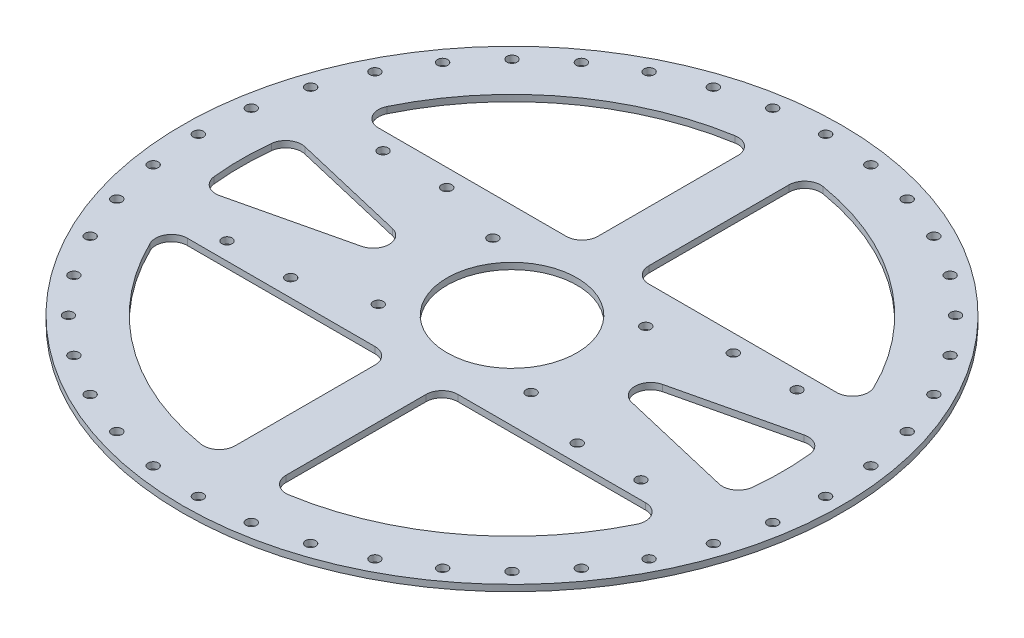
SolidWorks part; units mm, degrees
material "Thornel Mat VMA"
ref_plane "前视基准面" through (0, 0, 0) normal (0, 0, 1) x (1, 0, 0)
ref_plane "上视基准面" through (0, 0, 0) normal (0, 1, 0) x (1, 0, 0)
ref_plane "右视基准面" through (0, 0, 0) normal (1, 0, 0) x (0, 0, -1)
sketch "草图1" plane through (0, 0, 0) normal (0, 1, 0) x (1, 0, 0)
  line L1 (-24, 18) -> (24, 18) construction
  line L2 (-24, 18) -> (-24, -18) construction
  line L3 (-24, -18) -> (24, -18) construction
  line L4 (24, 18) -> (24, -18) construction
  line L5 (-24, 18) -> (24, -18) construction
  line L6 (-24, -18) -> (24, 18) construction
  circle A0 centre (-24, -18) radius 1.6
  circle A1 centre (24, -18) radius 1.6
  circle A2 centre (24, 18) radius 1.6
  circle A3 centre (-24, 18) radius 1.6
  circle A4 centre (0, 0) radius 103.5
  point P0 (0, 0)
  dimension "D3" = 3.2
  dimension "D4" = 207
  dimension "D1" = 48
  dimension "D2" = 36
extrude "凸台-拉伸1" add sketch "草图1" along normal blind 2
sketch "草图2" plane through (0, 2, 0) normal (0, 1, 0) x (1, 0, 0)
  line L0 (-55, 0) -> (55, 0) construction
  line L1 (-55, -24.5) -> (55, -24.5) construction
  line L2 (-55, 24.5) -> (55, 24.5) construction
  line L3 (-100, 0) -> (55, 0) construction
  line L4 (-100, -24.5) -> (55, -24.5) construction
  line L5 (-100, 24.5) -> (55, 24.5) construction
  line L6 (-65, 24.5) -> (-45, 24.5) construction
  line L7 (45, 24.5) -> (65, 24.5) construction
  line L8 (65, -24.5) -> (45, -24.5) construction
  line L9 (-65, -24.5) -> (-45, -24.5) construction
  circle A0 centre (0, 0) radius 98.5 construction
  circle A1 centre (-45, 24.5) radius 1.6
  circle A2 centre (-65, 24.5) radius 1.6
  circle A3 centre (-65, -24.5) radius 1.6
  circle A4 centre (-45, -24.5) radius 1.6
  circle A5 centre (45, -24.5) radius 1.6
  circle A6 centre (65, -24.5) radius 1.6
  circle A7 centre (45, 24.5) radius 1.6
  circle A8 centre (65, 24.5) radius 1.6
  circle A9 centre (0, 98.5) radius 1.6
  circle A10 centre (15.4088, 97.2873) radius 1.6
  circle A11 centre (30.4382, 93.6791) radius 1.6
  circle A12 centre (44.7181, 87.7641) radius 1.6
  circle A13 centre (57.8968, 79.6882) radius 1.6
  circle A14 centre (69.65, 69.65) radius 1.6
  circle A15 centre (79.6882, 57.8968) radius 1.6
  circle A16 centre (87.7641, 44.7181) radius 1.6
  circle A17 centre (93.6791, 30.4382) radius 1.6
  circle A18 centre (97.2873, 15.4088) radius 1.6
  circle A19 centre (98.5, 0) radius 1.6
  circle A20 centre (97.2873, -15.4088) radius 1.6
  circle A21 centre (93.6791, -30.4382) radius 1.6
  circle A22 centre (87.7641, -44.7181) radius 1.6
  circle A23 centre (79.6882, -57.8968) radius 1.6
  circle A24 centre (69.65, -69.65) radius 1.6
  circle A25 centre (57.8968, -79.6882) radius 1.6
  circle A26 centre (44.7181, -87.7641) radius 1.6
  circle A27 centre (30.4382, -93.6791) radius 1.6
  circle A28 centre (15.4088, -97.2873) radius 1.6
  circle A29 centre (0, -98.5) radius 1.6
  circle A30 centre (-15.4088, -97.2873) radius 1.6
  circle A31 centre (-30.4382, -93.6791) radius 1.6
  circle A32 centre (-44.7181, -87.7641) radius 1.6
  circle A33 centre (-57.8968, -79.6882) radius 1.6
  circle A34 centre (-69.65, -69.65) radius 1.6
  circle A35 centre (-79.6882, -57.8968) radius 1.6
  circle A36 centre (-87.7641, -44.7181) radius 1.6
  circle A37 centre (-93.6791, -30.4382) radius 1.6
  circle A38 centre (-97.2873, -15.4088) radius 1.6
  circle A39 centre (-98.5, 0) radius 1.6
  circle A40 centre (-97.2873, 15.4088) radius 1.6
  circle A41 centre (-93.6791, 30.4382) radius 1.6
  circle A42 centre (-87.7641, 44.7181) radius 1.6
  circle A43 centre (-79.6882, 57.8968) radius 1.6
  circle A44 centre (-69.65, 69.65) radius 1.6
  circle A45 centre (-57.8968, 79.6882) radius 1.6
  circle A46 centre (-44.7181, 87.7641) radius 1.6
  circle A47 centre (-30.4382, 93.6791) radius 1.6
  circle A48 centre (-15.4088, 97.2873) radius 1.6
  point P32 (116.4998, -20.0917)
  point P33 (0, 0)
  point P111 (0, 0)
  dimension "D5" = 3.2
  dimension "D6" = 197
  dimension "D7" = 3.2
  dimension "D3" = 110
  dimension "D4" = 20
  dimension "D1" = 24.5
  dimension "D2" = 24.5
  dimension "D8" = 40
extrude "切除-拉伸1" cut sketch "草图2" against normal through all
sketch "草图3" plane through (0, 2, 0) normal (0, 1, 0) x (1, 0, 0)
  line L0 (0, -85) -> (0, 85)
  line L1 (-85, 0) -> (85, 0)
  line L2 (8, -85) -> (8, 85)
  line L3 (-85, -8) -> (85, -8)
  line L4 (-8, -85) -> (-8, 85)
  line L5 (-85, 8) -> (85, 8)
  line L6 (-85, -30) -> (85, -30)
  line L7 (-85, 30) -> (85, 30)
  circle A0 centre (-24, 18) radius 1.6 construction
  circle A1 centre (24, 18) radius 1.6 construction
  circle A2 centre (24, -18) radius 1.6 construction
  circle A3 centre (-24, -18) radius 1.6 construction
  circle A4 centre (-24, 18) radius 1.6 construction
  circle A5 centre (24, 18) radius 1.6 construction
  circle A6 centre (24, -18) radius 1.6 construction
  circle A7 centre (-24, -18) radius 1.6 construction
  circle A8 centre (-24, 18) radius 9.6
  circle A9 centre (24, 18) radius 9.6
  circle A10 centre (24, -18) radius 9.6
  circle A11 centre (-24, -18) radius 9.6
  circle A12 centre (0, 0) radius 20.4
  circle A13 centre (0, 0) radius 85
  dimension "D2" = 170
  dimension "D1" = 8
  dimension "D3" = 8
  dimension "D4" = 8
  dimension "D5" = 30
  dimension "D6" = 30
extrude "切除-拉伸2" cut sketch "草图3" against normal blind 10 contours L6 A13 L4 | L2 A13 L6 | L7 A13 L2 | L4 A13 L7 | L4 A12 L5 | L5 A12 L1 L4 | L1 A12 L3 L4 | L3 A12 L4 | L4 A12 L0 L3 | L0 A12 L2 L3 | L0 L3 L2 L1 | L4 L3 L0 L1 | L5 L4 L1 L0 | L5 L0 L1 L2 | L2 A12 L0 L5 | L0 A12 L4 L5 | L5 A12 L2 | L1 A12 L5 L2 | L3 A12 L1 L2 | L2 A12 L3
sketch "草图4" plane through (0, 0, 0) normal (0, -1, 0) x (1, 0, 0)
  line L0 (-83.8801, -14.6334) -> (81.5859, 24.3666)
  line L1 (-82.733, 19.5) -> (82.733, 19.5)
  line L3 (-82.733, -19.5) -> (82.733, -19.5)
  line L5 (-82.733, 19.5) -> (82.733, -19.5) construction
  line L6 (-82.733, -19.5) -> (82.733, 19.5) construction
  line L7 (-81.5859, 24.3666) -> (83.8801, -14.6334)
  line L8 (-81.5859, -24.3666) -> (83.8801, 14.6334)
  line L9 (-83.8801, 14.6334) -> (81.5859, -24.3666)
  circle A0 centre (65, 24.5) radius 1.6 construction
  circle A1 centre (0, 0) radius 85
  point P0 (0, 0)
  point P10 (0, 0)
  point P12 (82.733, -19.5)
  dimension "D2" = 170
  dimension "D1" = 5
  dimension "D3" = 5
  dimension "D4" = 5
extrude "切除-拉伸3" cut sketch "草图4" against normal blind 10 contours L9 A1 L0 | L7 A1 L8
fillet "圆角1" radius 5 18 edges at (-83.7368, 1, 14.5996) (-83.7368, 1, -14.5996) (-21.7949, 1, 0) (83.7368, 1, 14.5996) (21.7949, 1, 0) (83.7368, 1, -14.5996) (-8, 1, -84.6227) (-8, 1, 84.6227) (79.5299, 1, 30) (-79.5299, 1, 30) (79.5299, 1, -30) (-79.5299, 1, -30) (-8, 1, -30) (8, 1, 84.6227) (8, 1, -84.6227) (8, 1, -30) (8, 1, 30) (-8, 1, 30)
